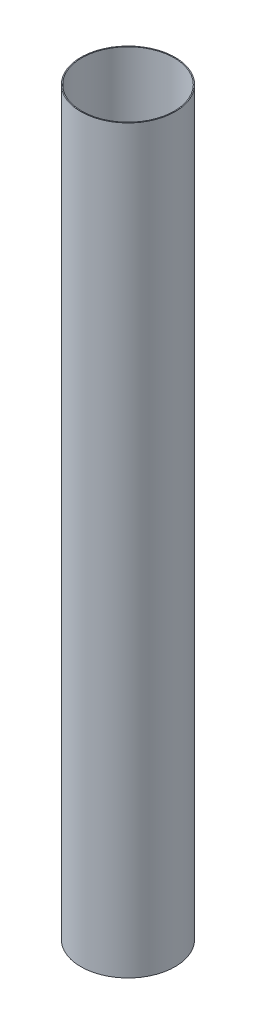
SolidWorks part; units mm, degrees
material "Hexcel AS4C (3000 Filaments)"
ref_plane "Front Plane" through (0, 0, 0) normal (0, 0, 1) x (1, 0, 0)
ref_plane "Top Plane" through (0, 0, 0) normal (0, 1, 0) x (1, 0, 0)
ref_plane "Right Plane" through (0, 0, 0) normal (1, 0, 0) x (0, 0, -1)
sketch "Sketch1" plane through (0, 0, 0) normal (0, 1, 0) x (1, 0, 0)
  circle A0 centre (0, 0) radius 97.028
  circle A1 centre (0, 0) radius 95.123
  dimension "D1" = 194.056
  dimension "D2" = 190.246
extrude "Boss-Extrude1" add sketch "Sketch1" along normal blind 1524
